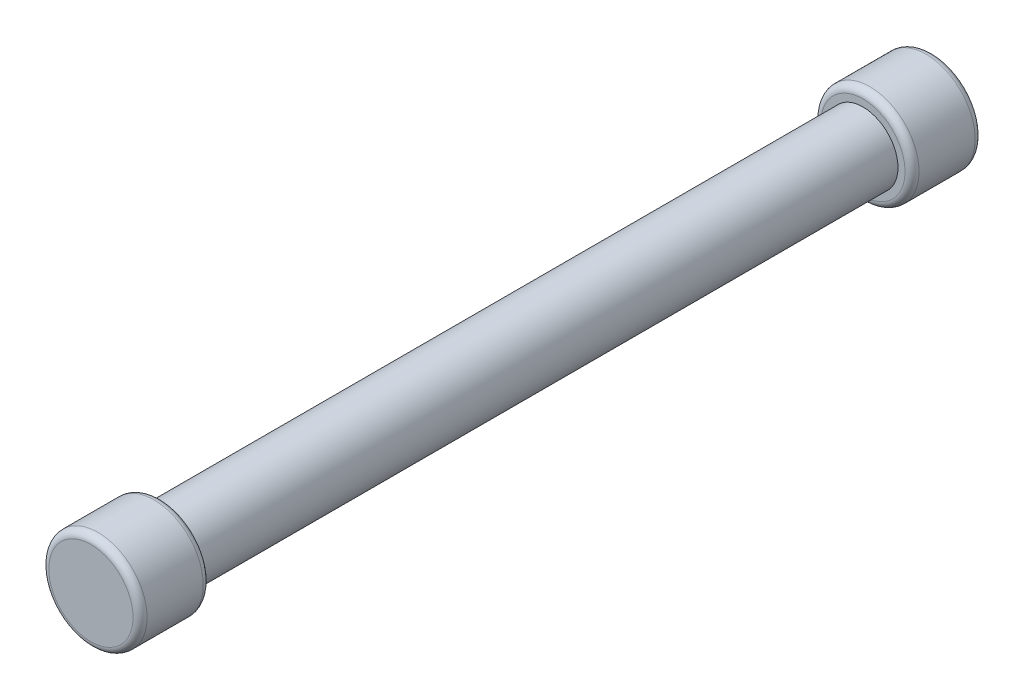
SolidWorks part; units mm, degrees
ref_plane "Front Plane" through (0, 0, 0) normal (0, 0, 1) x (1, 0, 0)
ref_plane "Top Plane" through (0, 0, 0) normal (0, 1, 0) x (1, 0, 0)
ref_plane "Right Plane" through (0, 0, 0) normal (1, 0, 0) x (0, 0, -1)
sketch "Sketch1" plane through (0, 0, 0) normal (0, 0, 1) x (1, 0, 0)
  circle A0 centre (0, 0) radius 3.5
  dimension "D1" = 7
extrude "Boss-Extrude1" add sketch "Sketch1" along normal blind 5
sketch "Sketch2" plane through (0, 0, 0) normal (0, 0, -1) x (-1, 0, 0)
  circle A0 centre (0, 0) radius 2.5
  dimension "D1" = 5
extrude "Boss-Extrude2" add sketch "Sketch2" along normal blind 50
sketch "Sketch3" plane through (0, 0, -50) normal (0, 0, -1) x (-1, 0, 0)
  circle A0 centre (0, 0) radius 3.5 construction
  circle A1 centre (0, 0) radius 3.5
extrude "Boss-Extrude3" add sketch "Sketch3" along normal blind 5
fillet "Fillet1" radius 0.5 4 edges at (3.5, 0, 5) (3.5, 0, 0) (-3.5, 0, -50) (-3.5, 0, -55)
